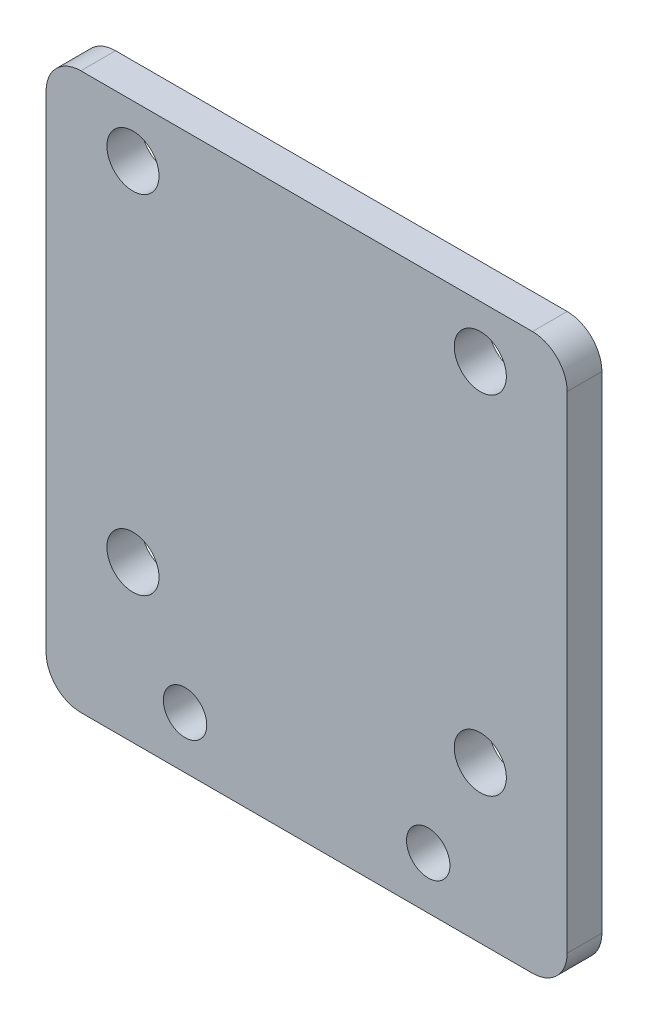
SolidWorks part; units mm, degrees
ref_plane "正面" through (0, 0, 0) normal (0, 0, 1) x (1, 0, 0)
ref_plane "平面" through (0, 0, 0) normal (0, 1, 0) x (1, 0, 0)
ref_plane "右側面" through (0, 0, 0) normal (1, 0, 0) x (0, 0, -1)
sketch "ｽｹｯﾁ1" plane through (0, 0, 0) normal (0, 0, 1) x (1, 0, 0)
  line L1 (-15, -16) -> (15, -16)
  line L2 (-15, -16) -> (-15, 16)
  line L3 (-15, 16) -> (15, 16)
  line L4 (15, -16) -> (15, 16)
  line L5 (-15, -16) -> (15, 16) construction
  line L6 (-15, 16) -> (15, -16) construction
  circle A0 centre (-7, -13) radius 1.25
  circle A1 centre (7, -13) radius 1.25
  circle A2 centre (-10, -7) radius 1.5
  circle A3 centre (-10, 13) radius 1.5
  circle A4 centre (10, 13) radius 1.5
  circle A5 centre (10, -7) radius 1.5
  point P0 (0, 0)
  dimension "D5" = 2.5
  dimension "D7" = 5
  dimension "D8" = 9
  dimension "D9" = 3
  dimension "D1" = 32
  dimension "D2" = 30
  dimension "D3" = 8
  dimension "D4" = 3
  dimension "D6" = 8
  dimension "D10" = 5
  dimension "D11" = 20
extrude "ﾎﾞｽ - 押し出し1" add sketch "ｽｹｯﾁ1" along normal blind 2
fillet "ﾌｨﾚｯﾄ1" radius 2 4 edges at (15, -16, 1) (-15, -16, 1) (15, 16, 1) (-15, 16, 1)
